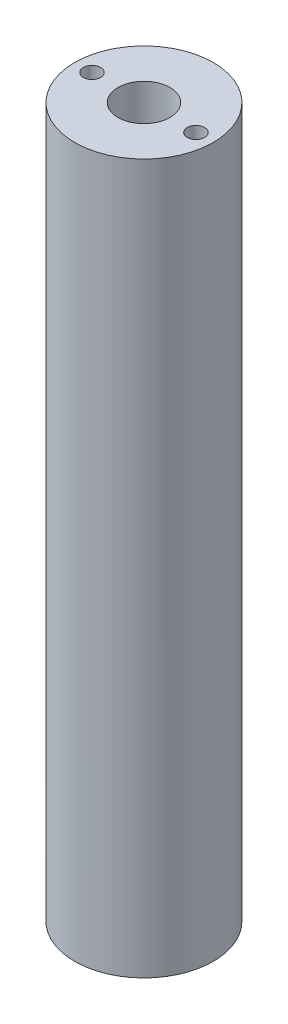
SolidWorks part; units mm, degrees
ref_plane "Front Plane" through (0, 0, 0) normal (0, 0, 1) x (1, 0, 0)
ref_plane "Top Plane" through (0, 0, 0) normal (0, 1, 0) x (1, 0, 0)
ref_plane "Right Plane" through (0, 0, 0) normal (1, 0, 0) x (0, 0, -1)
sketch "Sketch1" plane through (0, 0, 0) normal (0, 0, 1) x (1, 0, 0)
  line L1 (88.6061, 318.4272) -> (101.3061, 318.4272)
  line L2 (88.6061, 318.4272) -> (88.6061, 58.489)
  line L3 (88.6061, 58.489) -> (101.3061, 58.489)
  line L4 (101.3061, 318.4272) -> (101.3061, 58.489)
  dimension "D1" = 12.7
revolve "Revolve1" add sketch "Sketch1" angle 360 about L4
sketch "Sketch2" plane through (0, 318.4272, 0) normal (0, 1, 0) x (1, 0, 0)
  circle A0 centre (101.3061, 0) radius 4.7625
  dimension "D1" = 9.525
extrude "Cut-Extrude1" cut sketch "Sketch2" against normal through all
sketch "Sketch3" plane through (0, 0, 0) normal (0, 0, 1) x (1, 0, 0)
  line L0 (52.6227, 188.4581) -> (135.1428, 188.4581)
  line L2 (88.6061, 318.4272) -> (88.6061, 58.489) construction
  line L3 (52.6227, 188.4581) -> (52.6227, 329.3292)
  line L4 (52.6227, 329.3292) -> (135.1428, 329.3292)
  line L5 (135.1428, 329.3292) -> (135.1428, 188.4581)
  point P2 (88.6061, 188.4581)
extrude "Cut-Extrude2" cut sketch "Sketch3" against normal through all and the other way through all
sketch "Sketch4" plane through (0, 188.4581, 0) normal (0, 1, 0) x (1, 0, 0)
  circle A0 centre (91.7811, 0) radius 1.5875
  circle A1 centre (110.8311, 0) radius 1.5875
  circle A2 centre (101.3061, 0) radius 4.7625 construction
  dimension "D1" = 3.175
  dimension "D2" = 9.525
  dimension "D3" = 9.525
extrude "Cut-Extrude3" cut sketch "Sketch4" against normal blind 12.7
sketch "Sketch5" plane through (0, 58.489, 0) normal (0, -1, 0) x (1, 0, 0)
  circle A0 centre (91.7811, 0) radius 1.5875
  circle A1 centre (110.8311, 0) radius 1.5875
  circle A2 centre (101.3061, 0) radius 4.7625 construction
  dimension "D1" = 9.525
  dimension "D2" = 9.525
  dimension "D3" = 3.175
  dimension "D4" = 3.175
extrude "Cut-Extrude4" cut sketch "Sketch5" against normal blind 12.7
